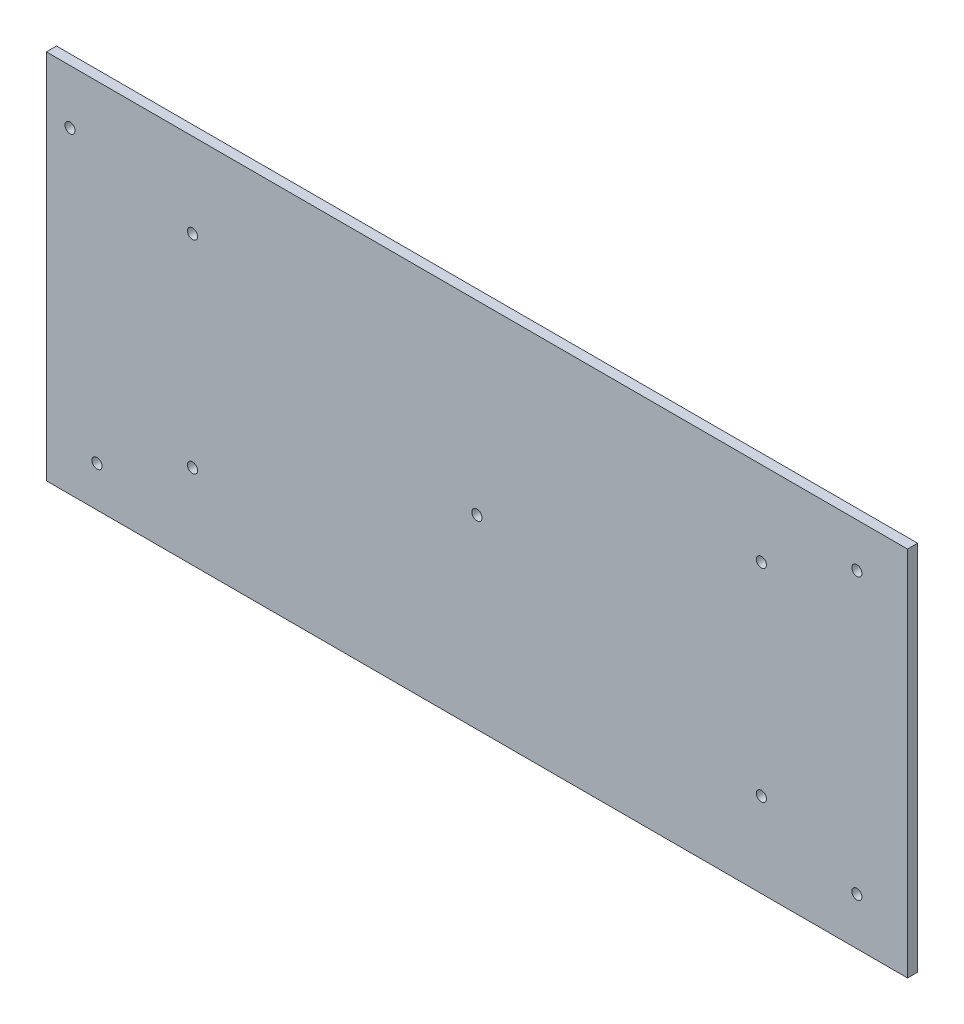
SolidWorks part; units mm, degrees
ref_plane "Front Plane" through (0, 0, 0) normal (0, 0, 1) x (1, 0, 0)
ref_plane "Top Plane" through (0, 0, 0) normal (0, 1, 0) x (1, 0, 0)
ref_plane "Right Plane" through (0, 0, 0) normal (1, 0, 0) x (0, 0, -1)
sketch "Sketch1" plane through (0, 0, 0) normal (0, 0, 1) x (1, 0, 0)
  line L0 (-140.6364, 23.6818) -> (114.3636, 23.6818) construction
  line L1 (-140.6364, 48.6818) -> (114.3636, 48.6818)
  line L2 (-140.6364, 48.6818) -> (-140.6364, -61.3182)
  line L3 (-140.6364, -61.3182) -> (114.3636, -61.3182)
  line L4 (114.3636, 48.6818) -> (114.3636, -61.3182)
  line L5 (-140.6364, -6.3182) -> (114.3636, -6.3182) construction
  line L6 (-140.6364, -36.3182) -> (114.3636, -36.3182) construction
  line L7 (-13.1364, 48.6818) -> (-13.1364, -61.3182) construction
  circle A0 centre (-125.6364, -49.3182) radius 1.5
  circle A1 centre (-133.6364, 32.6818) radius 1.5
  circle A2 centre (99.3636, -47.3182) radius 1.5
  circle A3 centre (99.3636, 35.6818) radius 1.5
  circle A4 centre (-97.3692, 23.6818) radius 1.5
  circle A5 centre (-97.3692, -36.3182) radius 1.5
  circle A6 centre (71.0965, -36.3182) radius 1.5
  circle A7 centre (71.0965, 23.6818) radius 1.5
  circle A8 centre (-13.1364, -6.3182) radius 1.5
  dimension "D11" = 3
  dimension "D12" = 3
  dimension "D13" = 3
  dimension "D14" = 3
  dimension "D16" = 3
  dimension "D17" = 3
  dimension "D18" = 3
  dimension "D1" = 255
  dimension "D2" = 110
  dimension "D3" = 240
  dimension "D4" = 248
  dimension "D5" = 15
  dimension "D6" = 15
  dimension "D7" = 16
  dimension "D8" = 12
  dimension "D9" = 14
  dimension "D10" = 13
  dimension "D15" = 30
extrude "Boss-Extrude1" add sketch "Sketch1" along normal blind 3
